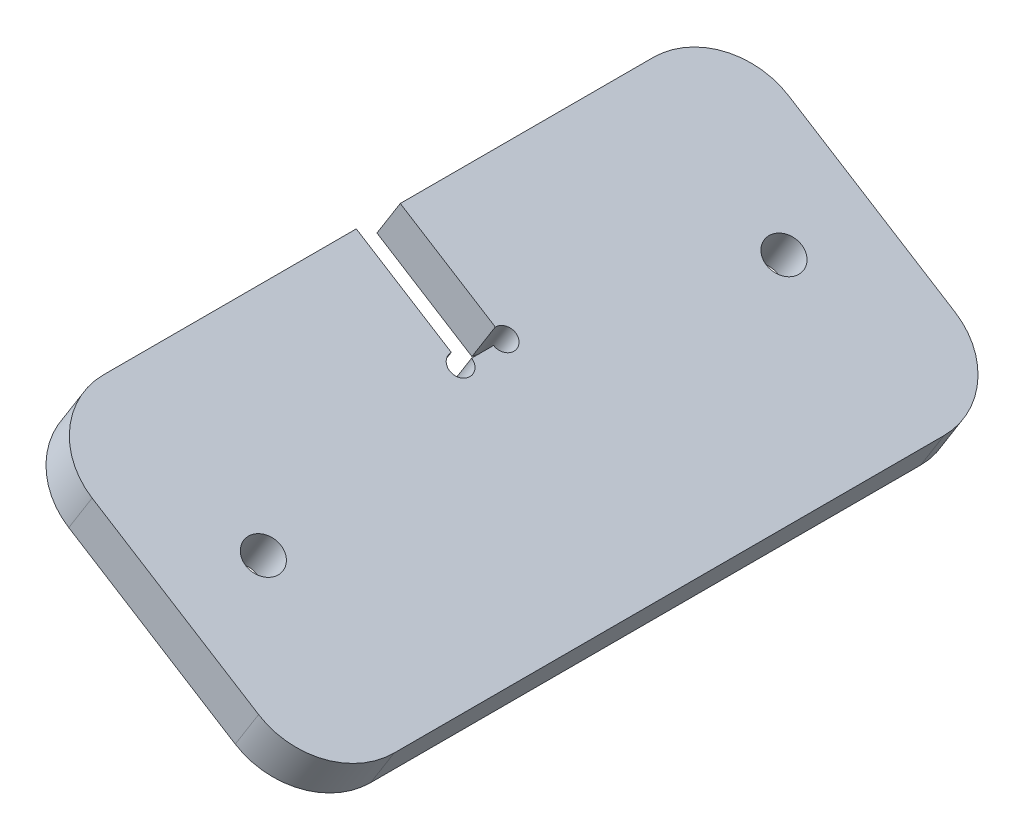
SolidWorks part; units mm, degrees
material "Plain Carbon Steel"
ref_plane "Front Plane" through (0, 0, 0) normal (0, 0, 1) x (1, 0, 0)
ref_plane "Top Plane" through (0, 0, 0) normal (0, 1, 0) x (1, 0, 0)
ref_plane "Right Plane" through (0, 0, 0) normal (1, 0, 0) x (0, 0, -1)
sketch "Sketch1" plane through (0, 0, -25) normal (0, 0, 1) x (1, 0, 0)
  line L0 (724, 137.9209) -> (698.5732, 153.8419)
  line L1 (698.5732, 153.8419) -> (701.7574, 158.9272)
  line L2 (724, 137.9209) -> (727.1842, 143.0062)
  line L3 (727.1842, 143.0062) -> (701.7574, 158.9272)
  line L6 (701.7574, 158.9272) -> (699.3693, 155.1132) construction
  line L7 (701.7574, 158.9272) -> (687.5307, 167.8353) construction
  line L10 (699.8446, 153.0458) -> (724, 137.9209) construction
extrude "Boss-Extrude1" add sketch "Sketch1" along normal up to surface (44.5 mm away) and the other way up to surface (50.5 mm away)
sketch "Sketch2" plane through (269.1304, 429.8171, 0) normal (0.5307, 0.8476, 0) x (0.8476, -0.5307, 0)
  line L0 (510.4385, 75.5) -> (493.653, 75.5)
  line L1 (493.653, 75.5) -> (493.653, 31)
  line L2 (493.653, -19.5) -> (510.4385, -19.5)
  line L3 (510.4385, -19.5) -> (510.4385, 25)
  line L4 (493.653, 31) -> (510.4385, 31) construction
  line L6 (493.653, 31) -> (510.4385, 31)
  line L7 (510.4385, 25) -> (493.653, 25) construction
  line L8 (493.653, 25) -> (510.4385, 25)
  line L10 (493.653, 25) -> (493.653, -19.5)
  line L11 (510.4385, 31) -> (510.4385, 75.5)
  line L12 (493.653, 31) -> (493.653, 25) construction
extrude "Boss-Extrude2" add sketch "Sketch2" against normal up to vertex (6 mm away)
fillet "Fillet1" radius 10 4 edges at (725.5921, 140.4635, -75.5) (685.9386, 165.2926, -75.5) (685.9386, 165.2926, 19.5) (725.5921, 140.4635, 19.5)
sketch "Sketch3" plane through (269.1304, 429.8171, 0) normal (0.5307, 0.8476, 0) x (0.8476, -0.5307, 0)
  line L0 (517.0457, -19.5) -> (517.0457, 75.5) construction
  line L1 (503.653, -19.5) -> (530.4385, -19.5) construction
  line L2 (503.653, 75.5) -> (530.4385, 75.5) construction
  line L3 (517.0457, 28) -> (540.4385, 28) construction
  line L4 (540.4385, -9.5) -> (540.4385, 65.5) construction
  circle A0 centre (510.4385, 25) radius 1.5
  circle A1 centre (510.4385, 31) radius 1.5
  circle A2 centre (517.0457, -7.5) radius 2.4
  circle A3 centre (517.0457, 63.5) radius 2.4
  dimension "D1" = 3
  dimension "D2" = 3
  dimension "D3" = 4.8
  dimension "D4" = 12
extrude "Cut-Extrude1" cut sketch "Sketch3" against normal through all
